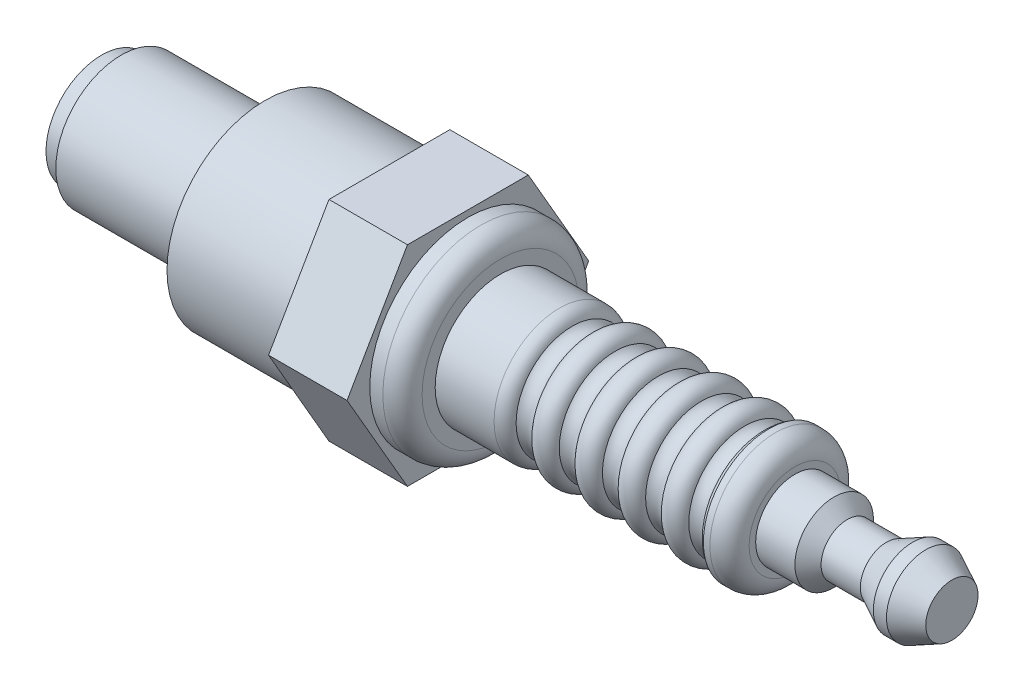
SolidWorks part; units mm, degrees
ref_plane "Plan1" through (0, 0, 0) normal (0, 0, 1) x (1, 0, 0)
ref_plane "Plan2" through (0, 0, 0) normal (0, 1, 0) x (1, 0, 0)
ref_plane "Plan3" through (0, 0, 0) normal (1, 0, 0) x (0, 0, -1)
sketch "Esquisse1" plane through (0, 0, 0) normal (0, 0, 1) x (1, 0, 0)
  line L0 (0, 0) -> (0, 4.25)
  line L1 (0, 4.25) -> (1.5, 4.25)
  line L2 (1.5, 4.25) -> (1.5, 5)
  line L3 (1.5, 5) -> (12.5, 5)
  line L4 (12.5, 5) -> (12.5, 7.5)
  line L5 (12.5, 7.5) -> (29, 7.5)
  line L6 (30.5, 6) -> (30.5, 5)
  line L7 (30.5, 5) -> (35.294, 5)
  line L8 (53, 3.5) -> (53, 3)
  line L9 (53, 3) -> (65, 3)
  line L10 (65, 3) -> (65, 0)
  line L11 (-10, 0) -> (120, 0) construction
  line L12 (35.294, 5) -> (51.5, 5)
  line L13 (0, 0) -> (65, 0)
  arc A10 (53, 3.5) -> (51.5, 5) centre (51.5, 3.5) ccw
  arc A11 (29, 7.5) -> (30.5, 6) centre (29, 6) cw
  point P18 (53, 5)
  point P50 (30.5, 7.5)
  dimension "D14" = 1.5
  dimension "D1" = 4.25
  dimension "D2" = 5
  dimension "D3" = 7.5
  dimension "D4" = 1.5
  dimension "D5" = 11
  dimension "D6" = 18
  dimension "D7" = 5
  dimension "D8" = 22.5
  dimension "D9" = 12
  dimension "D10" = 3
revolve "Base-Révolution" add sketch "Esquisse1" angle 360 about L11
cosmetic thread "Représentation de filetage1" parameters "D1"=10, "D2"=8
sketch "Esquisse2" plane through (0, 0, 0) normal (0, 0, 1) x (1, 0, 0)
  line L0 (51.5, 5) -> (30.5, 5) construction
  line L1 (60, 2) -> (62, 3)
  line L2 (35, 5) -> (34, 5)
  line L3 (-7, 0) -> (68, 0) construction
  line L4 (-10, 0) -> (120, 0) construction
  line L5 (-3.7, 0) -> (71.3, 0) construction
  line L6 (-0.4, 0) -> (74.6, 0) construction
  line L7 (2.9, 0) -> (77.9, 0) construction
  line L8 (51, 5) -> (51, 6)
  line L9 (51, 6) -> (34, 6)
  line L10 (34, 5) -> (34, 6)
  line L11 (57, 4) -> (60, 4)
  line L12 (57, 4) -> (56, 3)
  line L13 (57, 2) -> (60, 2)
  line L15 (57, 2) -> (56, 3)
  line L16 (62, 3) -> (63, 3)
  line L17 (65, 3) -> (53, 3) construction
  line L18 (63, 3) -> (65, 2)
  line L19 (65, 2) -> (65, 4)
  line L20 (65, 4) -> (60, 4)
  arc A0 (42.5615, 4.2747) -> (40.6385, 4.2747) centre (41.6, 4) ccw
  arc A1 (39.2615, 4.2747) -> (37.3385, 4.2747) centre (38.3, 4) ccw
  arc A2 (39.2615, 4.2747) -> (40.6385, 4.2747) centre (39.95, 5) ccw
  arc A3 (35.9615, 4.2747) -> (35, 5) centre (35, 4) ccw
  arc A4 (35.9615, 4.2747) -> (37.3385, 4.2747) centre (36.65, 5) ccw
  arc A5 (42.5615, 4.2747) -> (43.9385, 4.2747) centre (43.25, 5) ccw
  arc A6 (45.8615, 4.2747) -> (43.9385, 4.2747) centre (44.9, 4) ccw
  arc A7 (45.8615, 4.2747) -> (47.2385, 4.2747) centre (46.55, 5) ccw
  arc A8 (49.1615, 4.2747) -> (47.2385, 4.2747) centre (48.2, 4) ccw
  arc A9 (49.1615, 4.2747) -> (50.3936, 4.1606) centre (49.85, 5) ccw
  arc A10 (51, 5) -> (50.3936, 4.1606) centre (51.5, 4) ccw
  dimension "D1" = 3.3
  dimension "D2" = 2
  dimension "D5" = 2
  dimension "D7" = 2
  dimension "D8" = 3.3
  dimension "D9" = 4
  dimension "D10" = 35
revolve "Enlèvement de matière-Révolution1" cut sketch "Esquisse2" angle 360 about L3
ref_plane "Plan4" through (22, 0, 0) normal (1, 0, 0) x (0, 0, -1)
sketch "Esquisse3" plane through (22, 0, 0) normal (1, 0, 0) x (0, 0, -1)
  line L0 (-4.6188, 8) -> (4.6188, 8)
  line L1 (4.6188, 8) -> (9.2376, 0)
  line L2 (9.2376, 0) -> (4.6188, -8)
  line L3 (4.6188, -8) -> (-4.6188, -8)
  line L4 (-4.6188, -8) -> (-9.2376, 0)
  line L5 (-9.2376, 0) -> (-4.6188, 8)
  dimension "D1" = 8
extrude "Boss.-Extru.1" add sketch "Esquisse3" along normal blind 6
